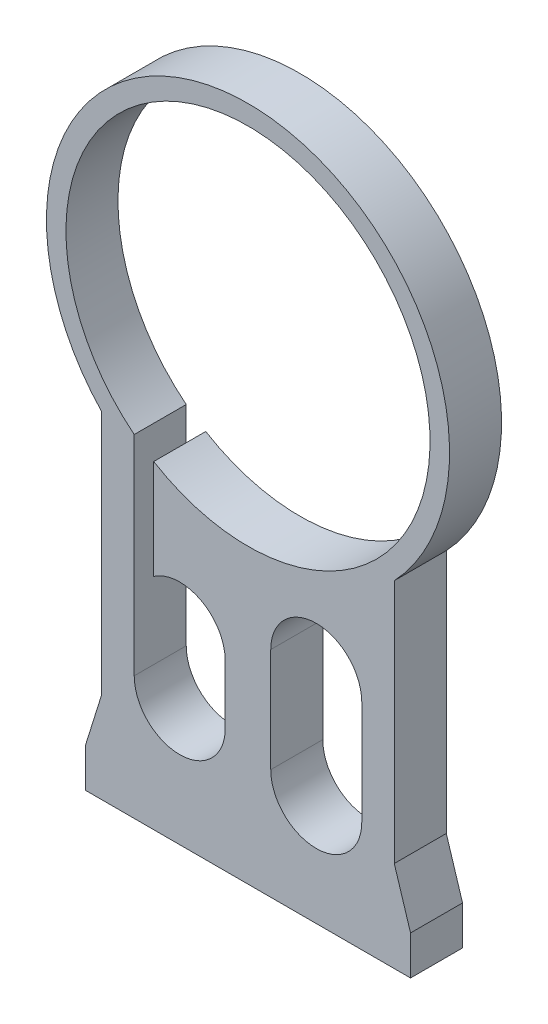
SolidWorks part; units mm, degrees
ref_plane "Płaszczyzna przednia" through (0, 0, 0) normal (0, 0, 1) x (1, 0, 0)
ref_plane "Płaszczyzna górna" through (0, 0, 0) normal (0, 1, 0) x (1, 0, 0)
ref_plane "Płaszczyzna prawa" through (0, 0, 0) normal (1, 0, 0) x (0, 0, -1)
sketch "Szkic1" plane through (0, 0, 0) normal (0, 0, 1) x (1, 0, 0)
  line L0 (0, 0) -> (0, 52) construction
  line L1 (12.5, 0) -> (-12.5, 0)
  line L2 (-12.5, 0) -> (-12.5, 3)
  line L3 (-12.5, 3) -> (-11.25, 7)
  line L4 (-11.25, 7) -> (-11.25, 25.8376)
  line L5 (5.25, 16.5) -> (5.25, 8.5) construction
  line L6 (8.75, 16.5) -> (8.75, 8.5)
  line L7 (1.75, 16.5) -> (1.75, 8.5)
  line L8 (12.5, 0) -> (12.5, 3)
  line L9 (12.5, 3) -> (11.25, 7)
  line L10 (11.25, 7) -> (11.25, 25.8376)
  line L11 (-5.25, 14) -> (-5.25, 9.5) construction
  line L12 (-1.75, 14) -> (-1.75, 9.5)
  line L13 (-8.75, 14) -> (-8.75, 9.5)
  line L14 (-8.75, 14) -> (-8.75, 25.5713)
  line L15 (-7.25, 24.5235) -> (-7.25, 16.8723)
  arc A1 (-7.25, 24.5235) -> (-8.75, 25.5713) centre (0, 36.5) ccw
  arc A2 (8.75, 16.5) -> (1.75, 16.5) centre (5.25, 16.5) ccw
  arc A3 (1.75, 8.5) -> (8.75, 8.5) centre (5.25, 8.5) ccw
  arc A4 (-1.75, 14) -> (-7.25, 16.8723) centre (-5.25, 14) ccw
  arc A5 (-8.75, 9.5) -> (-1.75, 9.5) centre (-5.25, 9.5) ccw
  arc A6 (11.25, 25.8376) -> (-11.25, 25.8376) centre (0, 36.5) ccw
  point P12 (5.25, 12.5)
  point P17 (5.25, 20)
  point P18 (5.25, 5)
  point P25 (-5.25, 11.75)
  point P31 (-5.25, 6)
  dimension "D1" = 3
  dimension "D5" = 15
  dimension "D9" = 28
  dimension "D2" = 4
  dimension "D3" = 11.25
  dimension "D4" = 7
  dimension "D6" = 5
  dimension "D7" = 52
  dimension "D10" = 2.5
  dimension "D11" = 7
  dimension "D12" = 2.5
  dimension "D14" = 1
  dimension "D15" = 1.5
extrude "Dodanie-wyciągnięcie1" add sketch "Szkic1" along normal blind 4
